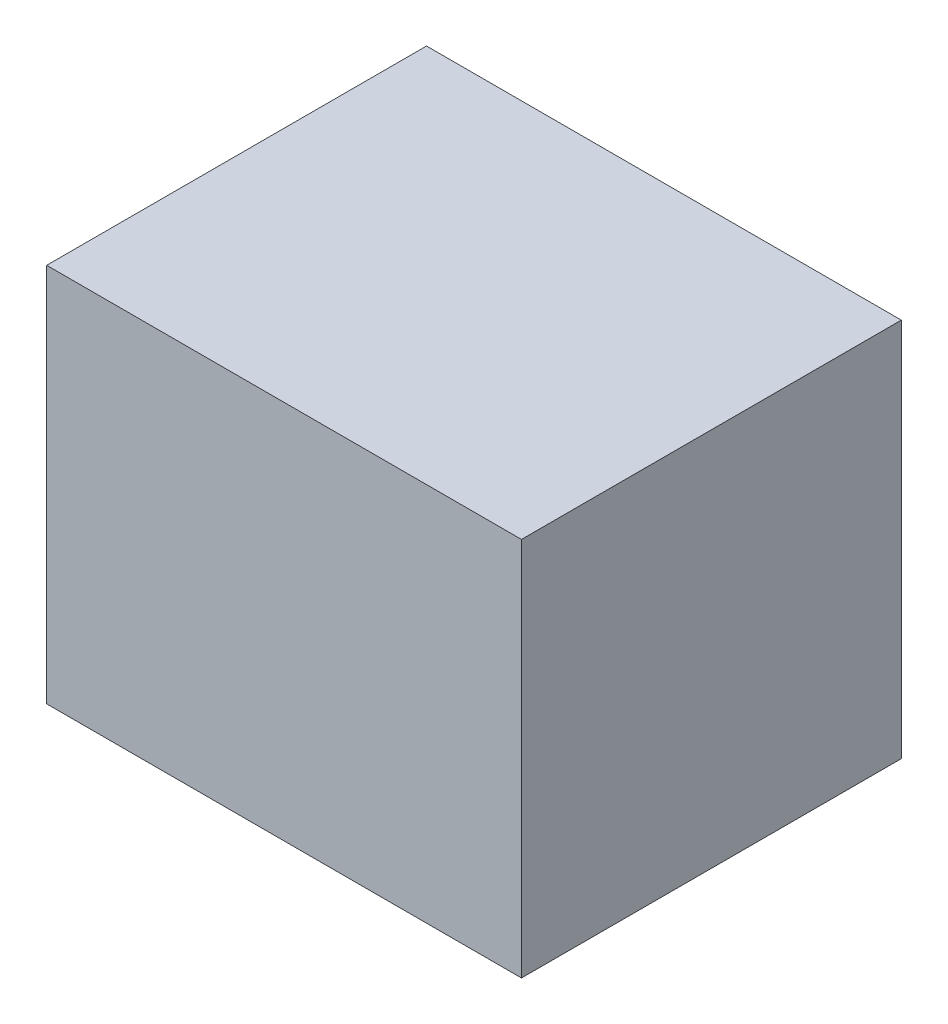
SolidWorks part; units mm, degrees
ref_plane "Front Plane" through (0, 0, 0) normal (0, 0, 1) x (1, 0, 0)
ref_plane "Top Plane" through (0, 0, 0) normal (0, 1, 0) x (1, 0, 0)
ref_plane "Right Plane" through (0, 0, 0) normal (1, 0, 0) x (0, 0, -1)
sketch "Sketch1" plane through (0, 0, 0) normal (0, 1, 0) x (1, 0, 0)
  line L1 (-63.5, -50.8) -> (63.5, -50.8)
  line L2 (-63.5, -50.8) -> (-63.5, 50.8)
  line L3 (-63.5, 50.8) -> (63.5, 50.8)
  line L4 (63.5, -50.8) -> (63.5, 50.8)
  line L5 (-63.5, -50.8) -> (63.5, 50.8) construction
  line L6 (-63.5, 50.8) -> (63.5, -50.8) construction
  point P0 (0, 0)
  dimension "D1" = 101.6
  dimension "D2" = 127
extrude "Boss-Extrude1" add sketch "Sketch1" along normal blind 101.6 contours L3 L4 L1 L2
